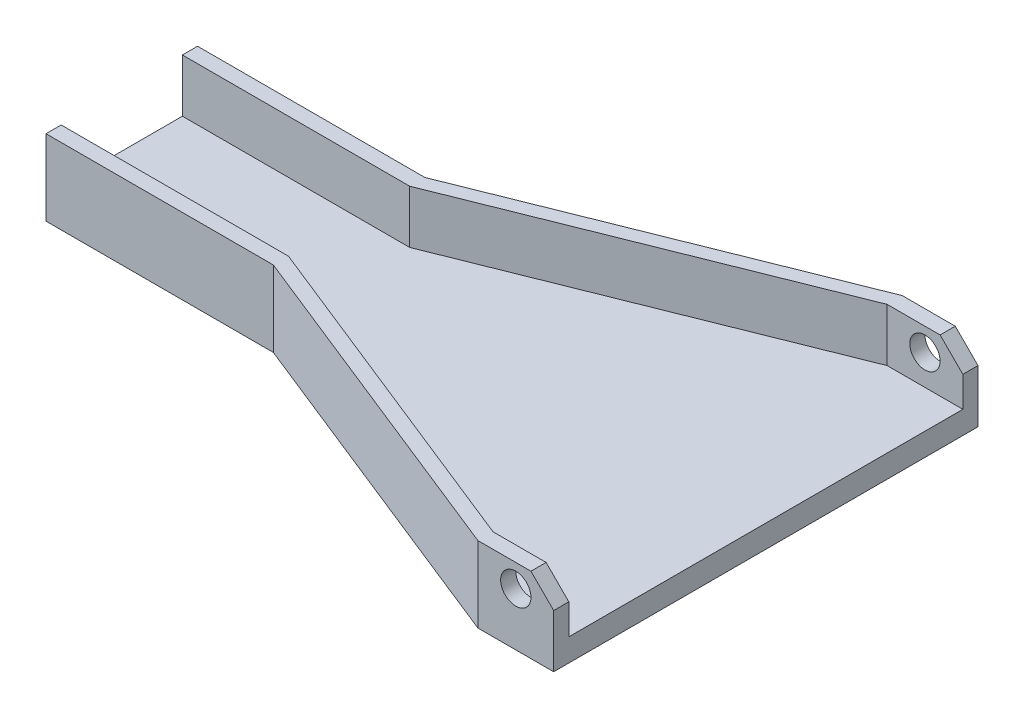
SolidWorks part; units mm, degrees
ref_plane "Alzado" through (0, 0, 0) normal (0, 0, 1) x (1, 0, 0)
ref_plane "Planta" through (0, 0, 0) normal (0, 1, 0) x (1, 0, 0)
ref_plane "Vista lateral" through (0, 0, 0) normal (1, 0, 0) x (0, 0, -1)
sketch "Croquis1" plane through (0, 0, 0) normal (0, 1, 0) x (1, 0, 0)
  line L1 (-15, -10) -> (15, -10)
  line L2 (-15, -10) -> (-15, 10)
  line L3 (-15, 10) -> (15, 10)
  line L5 (-15, -10) -> (15, 10) construction
  line L6 (-15, 10) -> (15, -10) construction
  line L9 (60, 28) -> (70, 28)
  line L13 (60, -28) -> (70, -28)
  line L14 (70, -28) -> (70, 28)
  line L15 (15, 10) -> (60, 28)
  line L16 (15, -10) -> (60, -28)
  line L17 (60, 28) -> (60, -28) construction
  point P0 (0, 0)
  point P13 (70, 0)
  dimension "D1" = 30
  dimension "D2" = 20
  dimension "D3" = 56
  dimension "D4" = 55
  dimension "D5" = 10
extrude "Saliente-Extruir1" add sketch "Croquis1" along normal blind 3
sketch "Croquis2" plane through (0, 3, 0) normal (0, 1, 0) x (1, 0, 0)
  line L0 (-15, 10) -> (15, 10)
  line L4 (60, 28) -> (70, 28)
  line L5 (70, 28) -> (70, 26)
  line L6 (70, -28) -> (70, 28) construction
  line L7 (70, 26) -> (60, 26)
  line L11 (15, 8) -> (-15, 8)
  line L12 (-15, 10) -> (-15, -10) construction
  line L13 (-15, 8) -> (-15, 10)
  line L14 (-15, -10) -> (15, -10)
  line L18 (60, -28) -> (70, -28)
  line L19 (-15, -10) -> (-15, -8)
  line L20 (-15, -8) -> (15, -8)
  line L24 (60, -26) -> (70, -26)
  line L25 (70, -26) -> (70, -28)
  line L26 (70, 28) -> (60, 28) construction
  line L27 (15, 10) -> (60, 28)
  line L28 (60, 26) -> (15, 8)
  line L29 (15, -8) -> (60, -26)
  line L30 (15, -10) -> (60, -28)
  point P2 (60.4509, 28)
  point P3 (0, 0)
  dimension "D1" = 2
  dimension "D2" = 2
  dimension "D4" = 2
  dimension "D5" = 2
extrude "Saliente-Extruir2" add sketch "Croquis2" along normal blind 7
sketch "Croquis3" plane through (0, 0, 28) normal (0, 0, 1) x (1, 0, 0)
  line L0 (60, 10) -> (70, 10) construction
  line L1 (70, 10) -> (70, 0) construction
  circle A0 centre (65, 7) radius 2
  point P4 (0, 0)
  dimension "D1" = 4
  dimension "D2" = 3
  dimension "D3" = 5
extrude "Cortar-Extruir1" cut sketch "Croquis3" against normal through all
chamfer "Chaflán1" distance 3 angle 45 2 edges at (70, 10, -27) (70, 10, 27)
